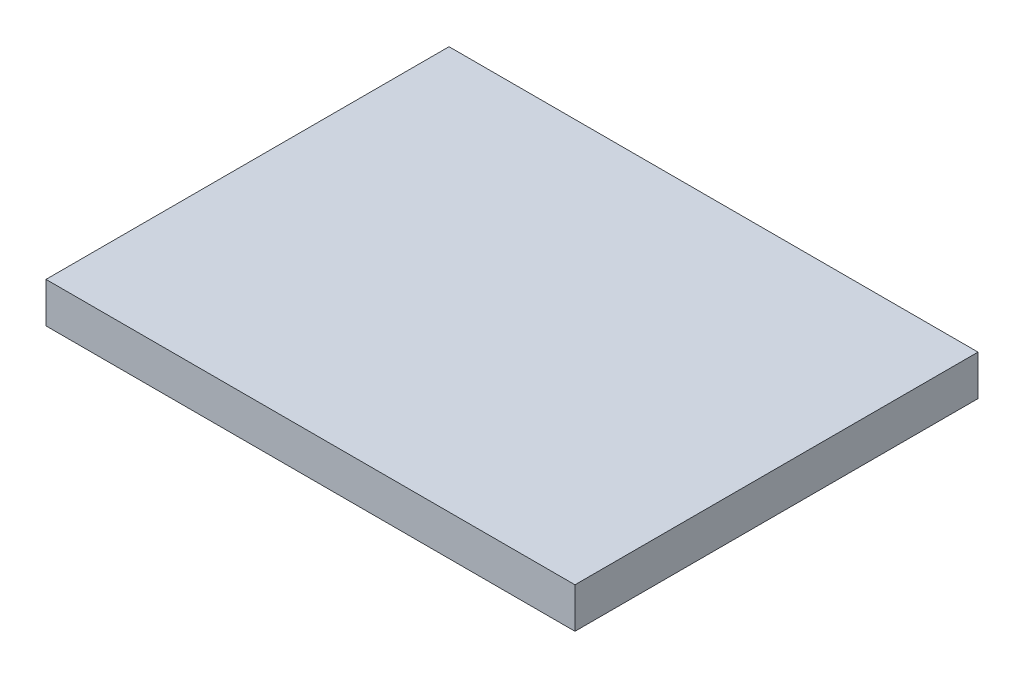
SolidWorks part; units mm, degrees
ref_plane "Front Plane" through (0, 0, 0) normal (0, 0, 1) x (1, 0, 0)
ref_plane "Top Plane" through (0, 0, 0) normal (0, 1, 0) x (1, 0, 0)
ref_plane "Right Plane" through (0, 0, 0) normal (1, 0, 0) x (0, 0, -1)
sketch "Sketch1" plane through (0, 0, 0) normal (0, 1, 0) x (1, 0, 0)
  line L1 (-10.5, -8) -> (10.5, -8)
  line L2 (-10.5, -8) -> (-10.5, 8)
  line L3 (-10.5, 8) -> (10.5, 8)
  line L4 (10.5, -8) -> (10.5, 8)
  line L5 (-10.5, -8) -> (10.5, 8) construction
  line L6 (-10.5, 8) -> (10.5, -8) construction
  point P0 (0, 0)
  dimension "D1" = 21
  dimension "D2" = 16
extrude "Boss-Extrude1" add sketch "Sketch1" along normal blind 1.6
